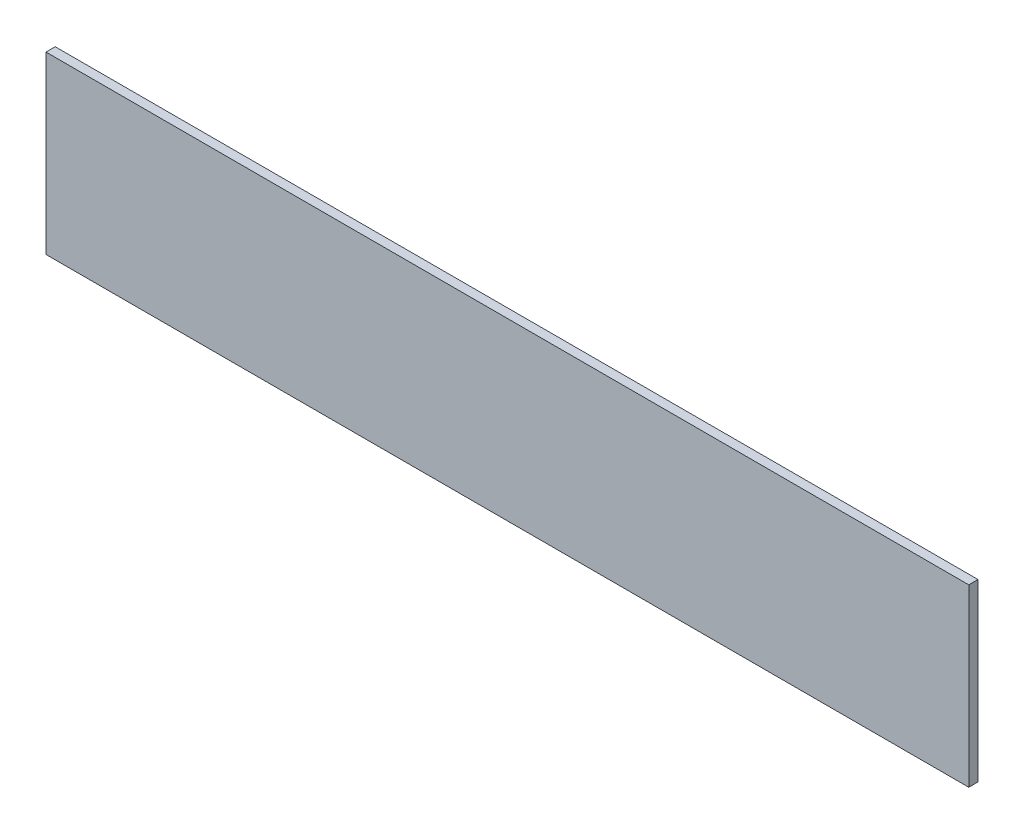
SolidWorks part; units mm, degrees
material "ABS PC"
ref_plane "前视基准面" through (0, 0, 0) normal (0, 0, 1) x (1, 0, 0)
ref_plane "上视基准面" through (0, 0, 0) normal (0, 1, 0) x (1, 0, 0)
ref_plane "右视基准面" through (0, 0, 0) normal (1, 0, 0) x (0, 0, -1)
other "Configuration Table"
sketch "草图1" plane through (0, 0, 0) normal (0, 0, 1) x (1, 0, 0)
  line L1 (-240.6015, 167.4134) -> (259.3985, 167.4134)
  line L2 (-240.6015, 167.4134) -> (-240.6015, 72.4134)
  line L3 (-240.6015, 72.4134) -> (259.3985, 72.4134)
  line L4 (259.3985, 167.4134) -> (259.3985, 72.4134)
  dimension "D1" = 500
  dimension "D2" = 95
extrude "凸台-拉伸1" add sketch "草图1" along normal blind 5
